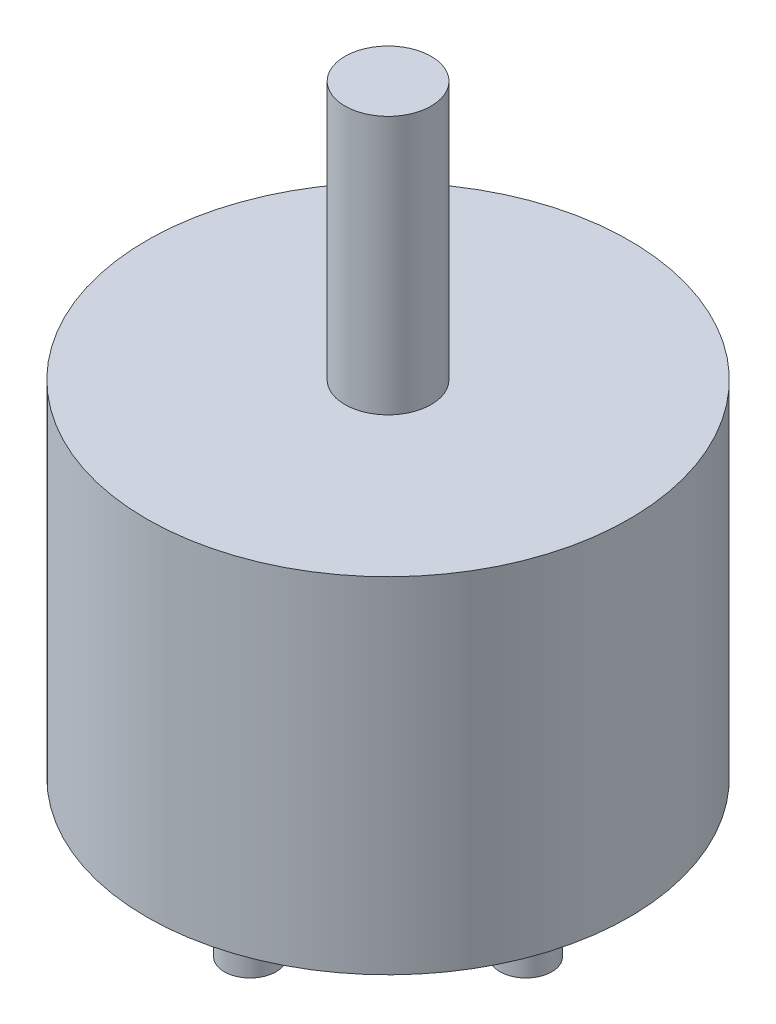
SolidWorks part; units mm, degrees
ref_plane "Plan de face" through (0, 0, 0) normal (0, 0, 1) x (1, 0, 0)
ref_plane "Plan de dessus" through (0, 0, 0) normal (0, 1, 0) x (1, 0, 0)
ref_plane "Plan de droite" through (0, 0, 0) normal (1, 0, 0) x (0, 0, -1)
sketch "Esquisse1" plane through (0, 0, 0) normal (0, 1, 0) x (1, 0, 0)
  circle A0 centre (0, 0) radius 14
extrude "Boss.-Extru.1" add sketch "Esquisse1" along normal blind 20
sketch "Esquisse2" plane through (0, 20, 0) normal (0, 1, 0) x (1, 0, 0)
  circle A0 centre (0, 0) radius 2.5
extrude "Boss.-Extru.2" add sketch "Esquisse2" along normal blind 15
sketch "Esquisse3" plane through (0, 0, 0) normal (0, -1, 0) x (-1, 0, 0)
  circle A1 centre (-8, 0) radius 1.5
  circle A2 centre (0, 8) radius 1.5
  circle A3 centre (8, 0) radius 1.4381
  circle A4 centre (0, -8) radius 1.5
  point P8 (0, 0)
  dimension "D1" = 8
  dimension "D2" = 8
  dimension "D4" = 8
  dimension "D3" = 8
extrude "Boss.-Extru.3" add sketch "Esquisse3" along normal blind 5
